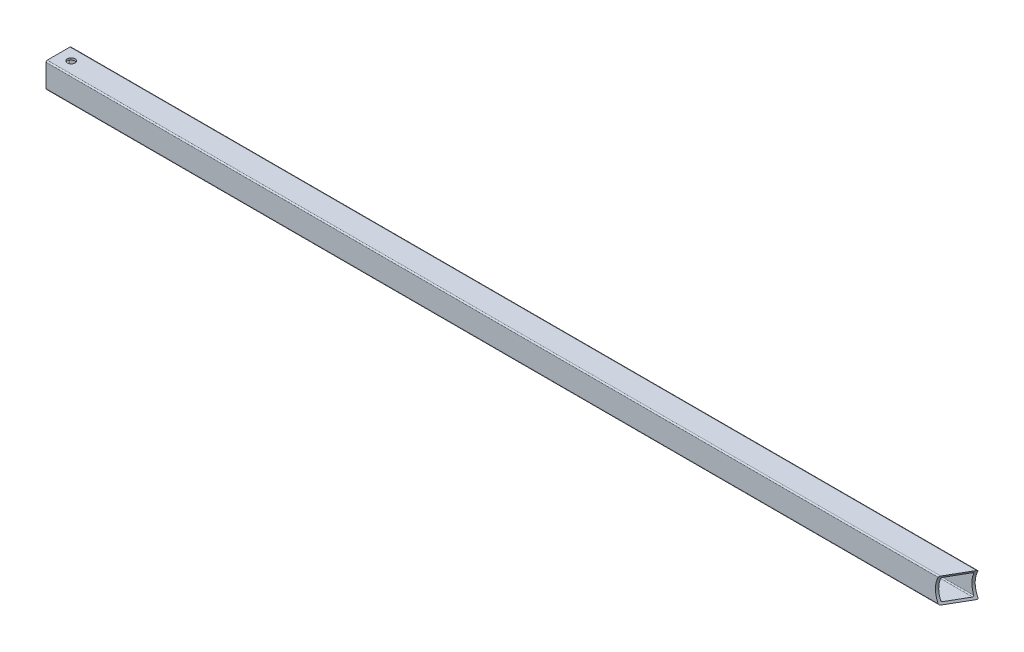
SolidWorks part; units mm, degrees
ref_plane "Front" through (0, 0, 0) normal (0, 0, 1) x (1, 0, 0)
ref_plane "Top" through (0, 0, 0) normal (0, 1, 0) x (1, 0, 0)
ref_plane "Right" through (0, 0, 0) normal (1, 0, 0) x (0, 0, -1)
sketch "Sketch1" plane through (0, 0, 0) normal (1, 0, 0) x (0, 0, -1)
  line L0 (-10.5918, 0) -> (-12.7, 0) construction
  line L1 (11.43, -12.7) -> (-11.43, -12.7) construction
  line L2 (12.7, -11.43) -> (12.7, 11.43) construction
  line L3 (11.43, 12.7) -> (-11.43, 12.7) construction
  line L4 (-12.7, -11.43) -> (-12.7, 11.43) construction
  line L5 (12.7, -12.7) -> (-12.7, 12.7) construction
  line L6 (12.7, 12.7) -> (-12.7, -12.7) construction
  line L7 (9.5326, 10.5918) -> (-9.5326, 10.5918) construction
  line L8 (10.5918, 9.5326) -> (10.5918, -9.5326) construction
  line L9 (9.5326, -10.5918) -> (-9.5326, -10.5918) construction
  line L10 (-10.5918, 9.5326) -> (-10.5918, -9.5326) construction
  line L11 (10.5918, 10.5918) -> (-10.5918, -10.5918) construction
  line L12 (10.5918, -10.5918) -> (-10.5918, 10.5918) construction
  line L13 (0, -10.5918) -> (0, -12.7) construction
  line L14 (10.5918, -9.5326) -> (10.5918, -12.7) construction
  line L15 (10.5918, 0) -> (12.7, 0) construction
  line L16 (10.5918, -12.7) -> (12.7, -12.7) construction
  arc A0 (-9.5326, -10.5918) -> (-10.5918, -9.5326) centre (-9.5326, -9.5326) cw construction
  arc A1 (10.5918, -9.5326) -> (9.5326, -10.5918) centre (9.5326, -9.5326) cw construction
  arc A2 (9.5326, 10.5918) -> (10.5918, 9.5326) centre (9.5326, 9.5326) cw construction
  arc A3 (-9.5326, 10.5918) -> (-10.5918, 9.5326) centre (-9.5326, 9.5326) ccw construction
  arc A4 (11.43, -12.7) -> (12.7, -11.43) centre (11.43, -11.43) ccw construction
  arc A5 (12.7, 11.43) -> (11.43, 12.7) centre (11.43, 11.43) ccw construction
  arc A6 (-11.43, 12.7) -> (-12.7, 11.43) centre (-11.43, 11.43) ccw construction
  arc A7 (-11.43, -12.7) -> (-12.7, -11.43) centre (-11.43, -11.43) cw construction
  point P0 (0, 0)
  point P6 (0, 0)
  dimension "D2" = 1.0592
  dimension "D3" = 1.27
  dimension "Outside Width" = 25.4
  dimension "Ouside Height" = 25.4
  dimension "Inside Height" = 21.1836
  dimension "Wall Thickness" = 2.1082
sketch "Sketch2" plane through (0, 0, 0) normal (0, 0, 1) x (1, 0, 0)
  line L0 (-457.2, 0) -> (457.2, 0) construction
  point P3 (-433.9082, 0)
  point P4 (433.9082, 0)
  dimension "Length" = 914.4
  dimension "D1" = 23.2918
  dimension "D2" = 23.2918
sketch "Sketch4" plane through (0, 0, 0) normal (1, 0, 0) x (0, 0, -1)
  line L8 (12.7, -11.43) -> (12.7, 11.43)
  line L9 (11.43, 12.7) -> (-11.43, 12.7)
  line L10 (-12.7, -11.43) -> (-12.7, 11.43)
  line L11 (11.43, -12.7) -> (-11.43, -12.7)
  line L12 (10.5918, 9.5326) -> (10.5918, -9.5326)
  line L13 (9.5326, -10.5918) -> (-9.5326, -10.5918)
  line L14 (-10.5918, 9.5326) -> (-10.5918, -9.5326)
  line L15 (9.5326, 10.5918) -> (-9.5326, 10.5918)
  arc A8 (12.7, 11.43) -> (11.43, 12.7) centre (11.43, 11.43) ccw
  arc A9 (-11.43, 12.7) -> (-12.7, 11.43) centre (-11.43, 11.43) ccw
  arc A10 (-12.7, -11.43) -> (-11.43, -12.7) centre (-11.43, -11.43) ccw
  arc A11 (11.43, -12.7) -> (12.7, -11.43) centre (11.43, -11.43) ccw
  arc A12 (9.5326, -10.5918) -> (10.5918, -9.5326) centre (9.5326, -9.5326) ccw
  arc A13 (-10.5918, -9.5326) -> (-9.5326, -10.5918) centre (-9.5326, -9.5326) ccw
  arc A14 (-9.5326, 10.5918) -> (-10.5918, 9.5326) centre (-9.5326, 9.5326) ccw
  arc A15 (10.5918, 9.5326) -> (9.5326, 10.5918) centre (9.5326, 9.5326) ccw
extrude "Boss-Extrude1" add sketch "Sketch4" along normal up to vertex (457.2 mm away) and the other way up to vertex (457.2 mm away)
sketch "Sketch5" plane through (0, 12.7, 0) normal (0, 1, 0) x (1, 0, 0)
  line L0 (-457.2, 11.43) -> (-457.2, -11.43) construction
  line L1 (457.2, -12.7) -> (-457.2, -12.7) construction
  circle A0 centre (-444.5, 0) radius 3.81
  dimension "D1" = 7.62
  dimension "D2" = 12.7
  dimension "D3" = 12.7
extrude "Cut-Extrude1" cut sketch "Sketch5" against normal through all
sketch "Sketch7" plane through (0, 12.7, 0) normal (0, 1, 0) x (1, 0, 0)
  line L0 (457.2, 12.7) -> (442.5353, -12.7)
  line L1 (457.2, -12.7) -> (-457.2, -12.7) construction
  line L2 (442.5353, -12.7) -> (457.2, -12.7)
  line L3 (457.2, -12.7) -> (457.2, 12.7)
  dimension "D1" = 60
extrude "Cut-Extrude2" cut sketch "Sketch7" against normal through all
ref_plane "Plane1" through (119.7993, 0, -207.4984) normal (0.5, 0, -0.866) x (0, 1, 0)
sketch "Sketch8" plane through (119.7993, 0, -207.4984) normal (0.5, 0, -0.866) x (0, 1, 0)
  line L0 (-11.43, 389.5968) -> (11.43, 389.5968) construction
  line L1 (-12.7, 389.5968) -> (-12.7, -401.6618) construction
  line L2 (12.7, 389.5968) -> (12.7, -401.6618) construction
  arc A0 (12.7, 389.5968) -> (-12.7, 389.5968) centre (0, 415.1945) cw
  point P5 (0, 0)
  point P8 (0, 0)
  dimension "D1" = 28.575
extrude "Cut-Extrude4" cut sketch "Sketch8" against normal through all and the other way through all flip side to cut
equation "\"D3@Sketch1\"=\"Outside Width@Sketch1\"*.05"
equation "\"D2@Sketch1\" = \"Inside Height@Sketch1\" * .05"
equation "\"D1@Sketch2\"=\"Outside Width@Sketch1\"-\"Wall Thickness@Sketch1\""
equation "\"D2@Sketch2\"=\"D1@Sketch2\""
